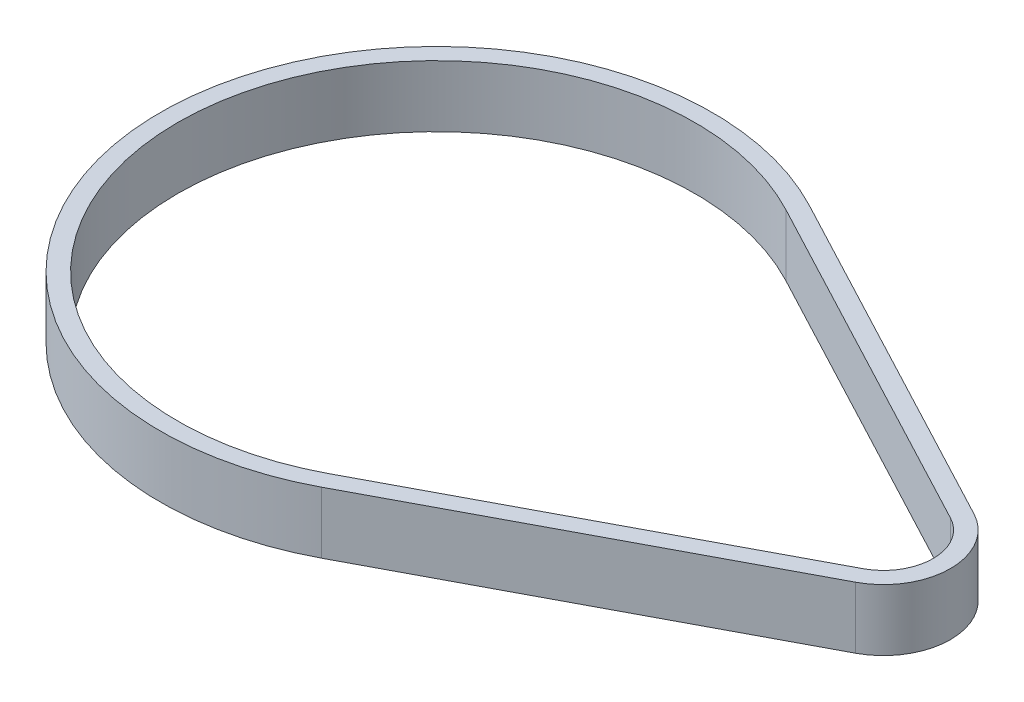
SolidWorks part; units mm, degrees
ref_plane "Front Plane" through (0, 0, 0) normal (0, 0, 1) x (1, 0, 0)
ref_plane "Top Plane" through (0, 0, 0) normal (0, 1, 0) x (1, 0, 0)
ref_plane "Right Plane" through (0, 0, 0) normal (1, 0, 0) x (0, 0, -1)
sketch "Sketch1" plane through (0, 0, 0) normal (0, 1, 0) x (1, 0, 0)
  line L0 (0, 0) -> (65.405, 0) construction
  line L1 (17.6821, 33.4376) -> (68.7942, 6.4091)
  line L2 (68.7942, -6.4091) -> (17.6821, -33.4376)
  line L3 (18.8695, 35.683) -> (69.9815, 8.6544)
  line L4 (69.9815, -8.6544) -> (18.8695, -35.683)
  arc A0 (17.6821, 33.4376) -> (17.6821, -33.4376) centre (0, 0) ccw
  arc A1 (68.7942, -6.4091) -> (68.7942, 6.4091) centre (65.405, 0) ccw
  arc A2 (69.9815, -8.6544) -> (69.9815, 8.6544) centre (65.405, 0) ccw
  arc A3 (18.8695, 35.683) -> (18.8695, -35.683) centre (0, 0) ccw
  dimension "D2" = 75.65
  dimension "D3" = 14.5
  dimension "D1" = 65.405
  dimension "D4" = 2.54
extrude "Boss-Extrude1" add sketch "Sketch1" along normal blind 9
